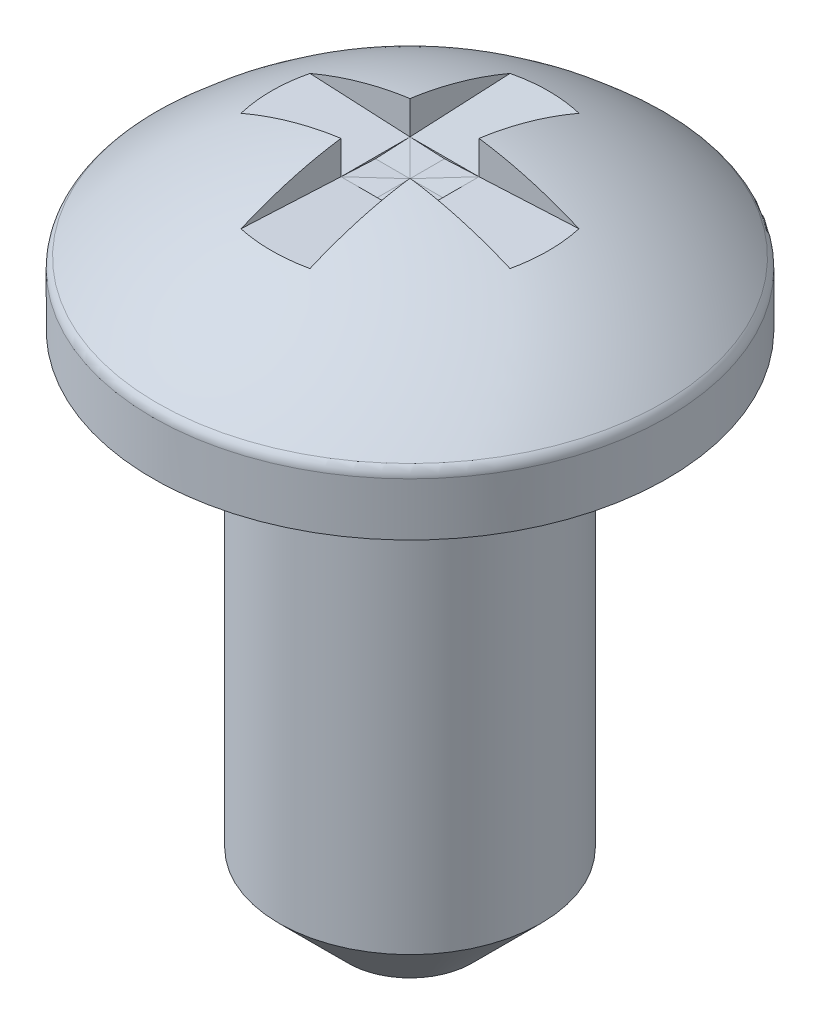
SolidWorks part; units mm, degrees
ref_plane "Front Plane" through (0, 0, 0) normal (0, 0, 1) x (1, 0, 0)
ref_plane "Top Plane" through (0, 0, 0) normal (0, 1, 0) x (1, 0, 0)
ref_plane "Right Plane" through (0, 0, 0) normal (1, 0, 0) x (0, 0, -1)
sketch "Sketch1" plane through (0, 0, 0) normal (0, 0, 1) x (1, 0, 0)
  line L0 (0, 0) -> (0, 12.7) construction
  line L1 (0, 0) -> (2.413, 0)
  line L2 (2.413, 0) -> (2.413, 9.525)
  line L3 (2.413, 9.525) -> (4.7371, 9.525)
  line L4 (4.7371, 9.525) -> (4.7371, 10.611)
  line L6 (0, 0) -> (0, 12.7)
  arc A0 (0, 12.7) -> (4.7371, 10.611) centre (-0.5668, 4.9992) cw
  dimension "D5" = 7.7216
  dimension "D1" = 12.7
  dimension "D2" = 4.826
  dimension "D3" = 9.4742
  dimension "D4" = 9.525
revolve "Revolve1" add sketch "Sketch1" angle 360 about L0
sketch "Sketch2" plane through (0, 0, 0) normal (0, 0, 1) x (1, 0, 0)
  line L0 (0, 12.7) -> (0, 11.938)
  line L1 (0, 11.938) -> (2.5488, 12.0644)
  arc A0 (4.7371, 10.611) -> (0, 12.7) centre (-0.5668, 4.9992) ccw construction
  arc A1 (2.5488, 12.0644) -> (0, 12.7) centre (-0.5668, 4.9992) ccw
  dimension "D1" = 0.762
extrude "Boss-Extrude1" cut sketch "Sketch2" against normal mid plane 1.27
pattern_circular "CirPattern1" count 4 over 360 about axis through (0, 0, 0) along (0, 1, 0) of "Boss-Extrude1"
fillet "Fillet1" radius 0.254 1 edges at (0, 10.611, -4.7371)
chamfer "Chamfer1" distance 1.27 angle 45 1 edges at (0, 0, -2.413)
